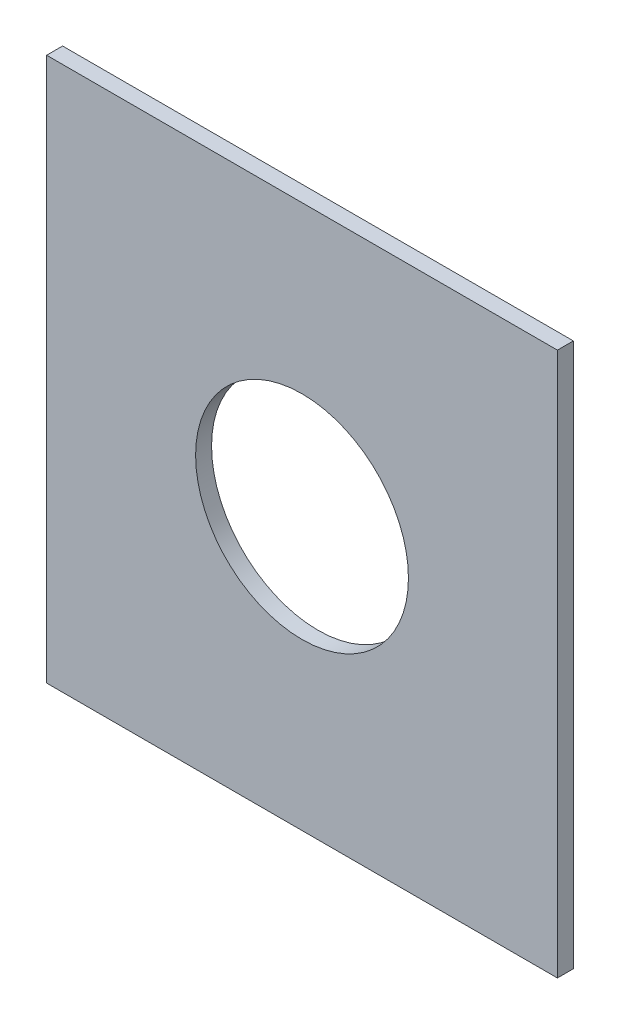
SolidWorks part; units mm, degrees
ref_plane "Front Plane" through (0, 0, 0) normal (0, 0, 1) x (1, 0, 0)
ref_plane "Top Plane" through (0, 0, 0) normal (0, 1, 0) x (1, 0, 0)
ref_plane "Right Plane" through (0, 0, 0) normal (1, 0, 0) x (0, 0, -1)
sketch "Sketch1" plane through (0, 0, 0) normal (0, 0, 1) x (1, 0, 0)
  line L0 (-285.7122, 240.5) -> (290.0853, 240.5) construction
  line L1 (-240, 255.5) -> (240, 255.5)
  line L2 (-240, 255.5) -> (-240, -255.5)
  line L3 (-240, -255.5) -> (240, -255.5)
  line L4 (240, 255.5) -> (240, -255.5)
  line L5 (-197, 283.5256) -> (-197, -327.2571) construction
  line L6 (-377.5483, -235.5) -> (335.2745, -235.5) construction
  line L7 (0, 621.1568) -> (0, -564.1033) construction
  dimension "D1" = 480
  dimension "D2" = 511
  dimension "D3" = 255.5
  dimension "D4" = 240
  dimension "D5" = 15
  dimension "D6" = 43
  dimension "D7" = 20
extrude "Boss-Extrude1" add sketch "Sketch1" along normal blind 15
sketch "Sketch3" plane through (0, 0, 0) normal (0, 0, -1) x (-1, 0, 0)
  circle A0 centre (0, 0) radius 100
  dimension "D1" = 200
extrude "Cut-Extrude2" cut sketch "Sketch3" against normal blind 15
sketch "Sketch4" plane through (0, 0, 0) normal (0, 0, -1) x (-1, 0, 0)
  line L0 (0, 0) -> (0, 296.6386) construction
  line L1 (0, 0) -> (203.6664, -117.5868) construction
  line L2 (0, 0) -> (-388.0138, -224.0199) construction
  line L3 (0, 0) -> (370.2851, 213.7842) construction
  line L4 (0, 0) -> (-391.4743, 226.0178) construction
  line L5 (0, 0) -> (0, -384.5891) construction
  line L6 (0, 0) -> (39.2781, 298.347) construction
  circle A0 centre (0, 0) radius 174.75 construction
  circle A1 centre (22.8095, 173.255) radius 1.5
  circle A2 centre (-22.8095, 173.255) radius 1.5
  circle A3 centre (-161.4479, -66.8739) radius 1.5
  circle A4 centre (-138.6385, -106.3811) radius 1.5
  circle A5 centre (138.6385, -106.3811) radius 1.5
  circle A6 centre (161.4479, -66.8739) radius 1.5
  dimension "D6" = 349.5
  dimension "D1" = 120
  dimension "D2" = 120
  dimension "D3" = 60
  dimension "D4" = 60
  dimension "D5" = 60
  dimension "D7" = 7.5
extrude "Cut-Extrude3" cut sketch "Sketch4" against normal blind 7
sketch "Sketch5" plane through (0, 0, 0) normal (0, 0, -1) x (-1, 0, 0)
  line L0 (0, 0) -> (0, 311.9546) construction
  line L1 (22.8095, 176.4304) -> (20.0595, 174.8427)
  line L2 (20.0595, 174.8427) -> (20.0595, 171.6673)
  line L3 (20.0595, 171.6673) -> (22.8095, 170.0796)
  line L4 (22.8095, 170.0796) -> (25.5595, 171.6673)
  line L5 (25.5595, 171.6673) -> (25.5595, 174.8427)
  line L6 (25.5595, 174.8427) -> (22.8095, 176.4304)
  line L7 (-20.0595, 174.8427) -> (-20.0595, 171.6673)
  line L8 (-20.0595, 171.6673) -> (-22.8095, 170.0796)
  line L9 (-22.8095, 170.0796) -> (-25.5595, 171.6673)
  line L10 (-25.5595, 171.6673) -> (-25.5595, 174.8427)
  line L11 (-25.5595, 174.8427) -> (-22.8095, 176.4304)
  line L12 (-22.8095, 176.4304) -> (-20.0595, 174.8427)
  line L13 (0, 0) -> (-333.48, 192.5348) construction
  line L14 (-164.1979, -68.4616) -> (-161.4479, -70.0494)
  line L15 (-164.1979, -65.2862) -> (-164.1979, -68.4616)
  line L16 (-161.4479, -63.6985) -> (-164.1979, -65.2862)
  line L17 (-158.6979, -65.2862) -> (-161.4479, -63.6985)
  line L18 (-158.6979, -68.4616) -> (-158.6979, -65.2862)
  line L19 (-161.4479, -70.0494) -> (-158.6979, -68.4616)
  line L20 (-138.6385, -109.5565) -> (-141.3885, -107.9688)
  line L21 (-135.8885, -107.9688) -> (-138.6385, -109.5565)
  line L22 (-135.8885, -104.7933) -> (-135.8885, -107.9688)
  line L23 (-138.6385, -103.2056) -> (-135.8885, -104.7933)
  line L24 (-141.3885, -104.7933) -> (-138.6385, -103.2056)
  line L25 (-141.3885, -107.9688) -> (-141.3885, -104.7933)
  line L26 (0, 0) -> (285.7658, 164.9869) construction
  line L27 (141.3885, -107.9688) -> (141.3885, -104.7933)
  line L28 (138.6385, -109.5565) -> (141.3885, -107.9688)
  line L29 (135.8885, -107.9688) -> (138.6385, -109.5565)
  line L30 (135.8885, -104.7933) -> (135.8885, -107.9688)
  line L31 (138.6385, -103.2056) -> (135.8885, -104.7933)
  line L32 (141.3885, -104.7933) -> (138.6385, -103.2056)
  line L33 (164.1979, -65.2862) -> (164.1979, -68.4616)
  line L34 (161.4479, -63.6985) -> (164.1979, -65.2862)
  line L35 (158.6979, -65.2862) -> (161.4479, -63.6985)
  line L36 (158.6979, -68.4616) -> (158.6979, -65.2862)
  line L37 (161.4479, -70.0494) -> (158.6979, -68.4616)
  line L38 (164.1979, -68.4616) -> (161.4479, -70.0494)
  circle A0 centre (22.8095, 173.255) radius 2.75 construction
  circle A1 centre (-138.6385, -106.3811) radius 2.75 construction
  circle A2 centre (161.4479, -66.8739) radius 2.75 construction
  dimension "D1" = 60
  dimension "D2" = 60
extrude "Cut-Extrude4" cut sketch "Sketch5" against normal blind 2.3
sketch "Sketch6" plane through (0, 0, 0) normal (0, 0, -1) x (-1, 0, 0)
  circle A0 centre (-156.9115, 135.0103) radius 40 construction
  circle A1 centre (0, 0) radius 165 construction
  circle A2 centre (-156.9115, 135.0103) radius 3
  dimension "D1" = 330
  dimension "D2" = 80
  dimension "D3" = 207
extrude "Cut-Extrude5" cut sketch "Sketch6" against normal blind 7
sketch "Sketch7" plane through (0, 0, 0) normal (0, 0, -1) x (-1, 0, 0)
  line L0 (-156.9115, 135.0103) -> (-156.9115, 182.5103) construction
  line L1 (-156.9115, 135.0103) -> (-110.4062, 181.5156) construction
  line L2 (-156.9115, 135.0103) -> (-210.5598, 188.6585) construction
  line L3 (-156.9115, 135.0103) -> (-190.4991, 101.4227) construction
  circle A0 centre (-156.9115, 135.0103) radius 47.5 construction
  circle A1 centre (-123.324, 168.5978) radius 1.5
  circle A2 centre (-190.4991, 168.5978) radius 1.5
  circle A3 centre (-190.4991, 101.4227) radius 1.5
  dimension "D1" = 95
  dimension "D5" = 3
  dimension "D6" = 3
  dimension "D7" = 3
  dimension "D2" = 45
  dimension "D3" = 45
  dimension "D4" = 90
extrude "Cut-Extrude6" cut sketch "Sketch7" against normal blind 5
